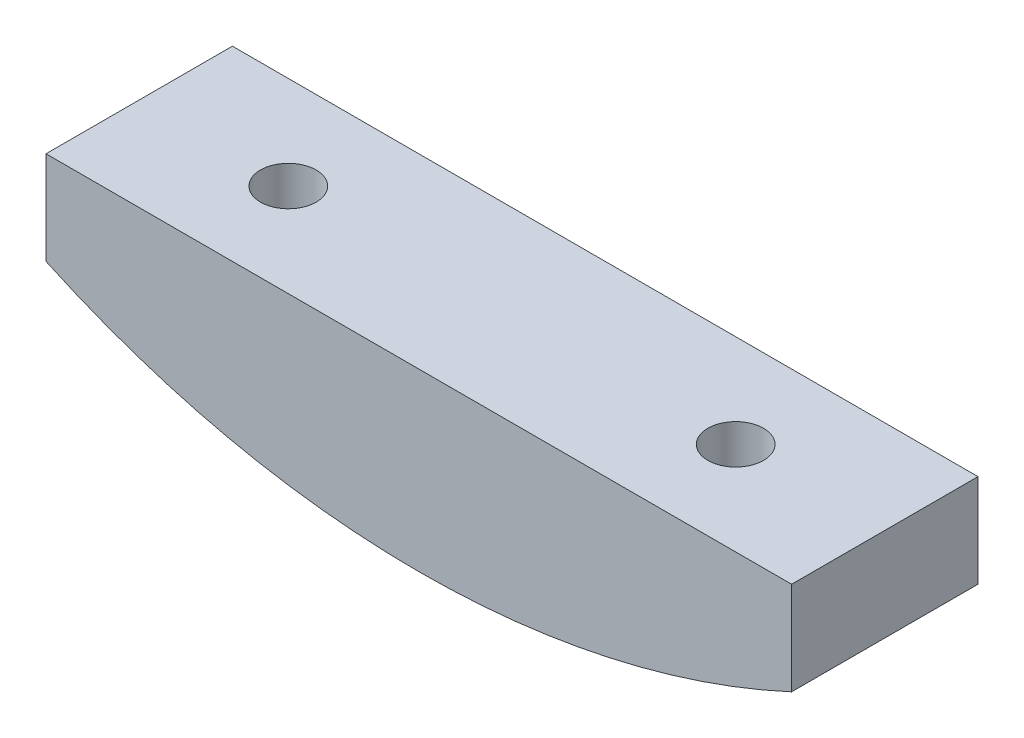
SolidWorks part; units mm, degrees
ref_plane "Front Plane" through (0, 0, 0) normal (0, 0, 1) x (1, 0, 0)
ref_plane "Top Plane" through (0, 0, 0) normal (0, 1, 0) x (1, 0, 0)
ref_plane "Right Plane" through (0, 0, 0) normal (1, 0, 0) x (0, 0, -1)
sketch "Sketch1" plane through (0, 0, 0) normal (0, 1, 0) x (1, 0, 0)
  line L1 (-25.4, -22.225) -> (25.4, -22.225)
  line L2 (-25.4, -22.225) -> (-25.4, 22.225)
  line L3 (-25.4, 22.225) -> (25.4, 22.225)
  line L4 (25.4, -22.225) -> (25.4, 22.225)
  line L5 (-25.4, -22.225) -> (25.4, 22.225) construction
  line L6 (-25.4, 22.225) -> (25.4, -22.225) construction
  point P0 (0, 0)
  dimension "D1" = 44.45
  dimension "D2" = 50.8
extrude "Boss-Extrude1" add sketch "Sketch1" along normal blind 6.35
sketch "Sketch2" plane through (0, 0, 22.225) normal (0, 0, 1) x (1, 0, 0)
  line L0 (-25.4, 0) -> (25.4, 0)
  arc A0 (-25.4, 0) -> (25.4, 0) centre (0, 54.717) ccw
  dimension "D1" = 60.325
extrude "Boss-Extrude2" add sketch "Sketch2" against normal blind 44.45
sketch "Sketch3" plane through (0, 6.35, 0) normal (0, 1, 0) x (1, 0, 0)
  line L0 (-25.4, 22.225) -> (-25.4, -22.225) construction
  line L1 (-25.4, -22.225) -> (25.4, -22.225) construction
  point P0 (-17.95, -14.65)
  point P1 (0, 14.65)
  point P2 (17.95, -14.65)
  dimension "D1" = 35.9
  dimension "D2" = 7.45
  dimension "D3" = 17.95
  dimension "D4" = 29.3
  dimension "D5" = 7.575
hole_wizard "M4x0.7 Tapped Hole1" positions "Sketch5" profile "Sketch4" tap size "M4x0.7" standard "ANSI Metric" end condition through all
sketch "Sketch5" plane through (0, 6.35, 0) normal (0, 1, 0) x (1, 0, 0)
  point P0 (0, 14.65)
  point P3 (-17.95, -14.65)
  point P6 (17.95, -14.65)
sketch "Sketch4" plane through (0, 6.35, -14.65) normal (1, 0, 0) x (0, 0, 1)
  line L0 (0, 0) -> (0, 11.958)
  line L1 (0, 11.958) -> (1.65, 11.958)
  line L2 (1.65, 11.958) -> (1.65, 0)
  line L5 (1.65, 0) -> (0, 0)
  line L11 (0, -6.35) -> (0, 107.95) construction
  dimension "Thru Tap Drill Dia." = 3.3
  dimension "Thru Tap Drill Depth" = 11.958
cosmetic thread "Hole Thread1" parameters "D2"=4
cosmetic thread "Hole Thread2" parameters "D2"=4
cosmetic thread "Hole Thread3" parameters "D2"=4
sketch "Sketch6" plane through (0, 0, -22.225) normal (0, 0, -1) x (-1, 0, 0)
  line L0 (-25.4, 6.35) -> (25.4, 6.35)
  line L1 (25.4, 6.35) -> (25.4, 0)
  line L2 (-25.4, 6.35) -> (-25.4, 0)
  arc A0 (-25.4, 0) -> (25.4, 0) centre (0, 54.717) ccw
  dimension "D1" = 60.325
extrude "Boss-Extrude3" add sketch "Sketch6" along normal blind 12.7
sketch "Sketch7" plane through (0, 6.35, 0) normal (0, 1, 0) x (1, 0, 0)
  line L0 (-25.4, 34.925) -> (25.4, 34.925) construction
  line L1 (-25.4, 34.925) -> (-25.4, -22.225) construction
  point P0 (-15.24, 28.575)
  point P1 (15.24, 28.575)
  dimension "D1" = 30.48
  dimension "D2" = 6.35
  dimension "D3" = 10.16
hole_wizard "#10-24 Tapped Hole1" positions "Sketch9" profile "Sketch8" tap size "#10-24" standard "ANSI Inch" end condition through all
sketch "Sketch9" plane through (0, 6.35, 0) normal (0, 1, 0) x (1, 0, 0)
  point P0 (-15.24, 28.575)
  point P3 (15.24, 28.575)
sketch "Sketch8" plane through (-15.24, 6.35, -28.575) normal (1, 0, 0) x (0, 0, 1)
  line L0 (0, 0) -> (0, 11.958)
  line L1 (0, 11.958) -> (1.8986, 11.958)
  line L2 (1.8986, 11.958) -> (1.8986, 0)
  line L5 (1.8986, 0) -> (0, 0)
  line L11 (0, -6.35) -> (0, 107.95) construction
  dimension "Thru Tap Drill Dia." = 3.7973
  dimension "Thru Tap Drill Depth" = 11.958
cosmetic thread "Hole Thread4" parameters "D2"=4.826
cosmetic thread "Hole Thread5" parameters "D2"=4.826
sketch "Sketch10" plane through (0, 6.35, 0) normal (0, 1, 0) x (1, 0, 0)
  line L0 (-25.4, 34.925) -> (-25.4, -22.225) construction
  line L1 (-25.4, 22.225) -> (25.4, 22.225)
  line L2 (-25.4, 22.225) -> (-25.4, -22.225)
  line L3 (-25.4, -22.225) -> (25.4, -22.225)
  line L4 (25.4, 22.225) -> (25.4, -22.225)
  line L5 (-25.4, 34.925) -> (25.4, 34.925) construction
  dimension "D1" = 12.7
extrude "Cut-Extrude1" cut sketch "Sketch10" against normal blind 25.4
